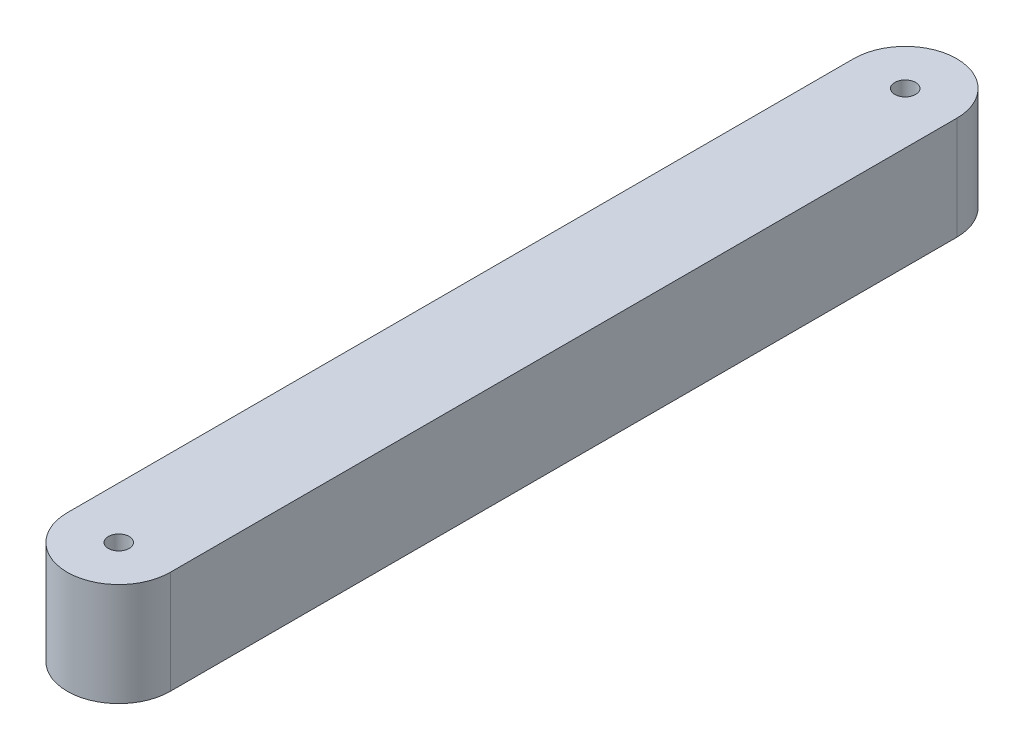
SolidWorks part; units mm, degrees
ref_plane "Front Plane" through (0, 0, 0) normal (0, 0, 1) x (1, 0, 0)
ref_plane "Top Plane" through (0, 0, 0) normal (0, 1, 0) x (1, 0, 0)
ref_plane "Right Plane" through (0, 0, 0) normal (1, 0, 0) x (0, 0, -1)
sketch "Sketch1" plane through (0, 0, 0) normal (0, 1, 0) x (1, 0, 0)
  line L0 (0, 0) -> (0, 152.5) construction
  line L1 (-10, 0) -> (-10, 152.5)
  line L2 (10, 0) -> (10, 152.5)
  arc A0 (-10, 0) -> (10, 0) centre (0, 0) ccw
  arc A1 (10, 152.5) -> (-10, 152.5) centre (0, 152.5) ccw
  circle A2 centre (0, 0) radius 2.0224
  circle A3 centre (0, 152.5) radius 2.0224
  point P3 (0, 76.25)
  dimension "D1" = 20
  dimension "D2" = 152.5
extrude "Boss-Extrude1" add sketch "Sketch1" along normal blind 20
